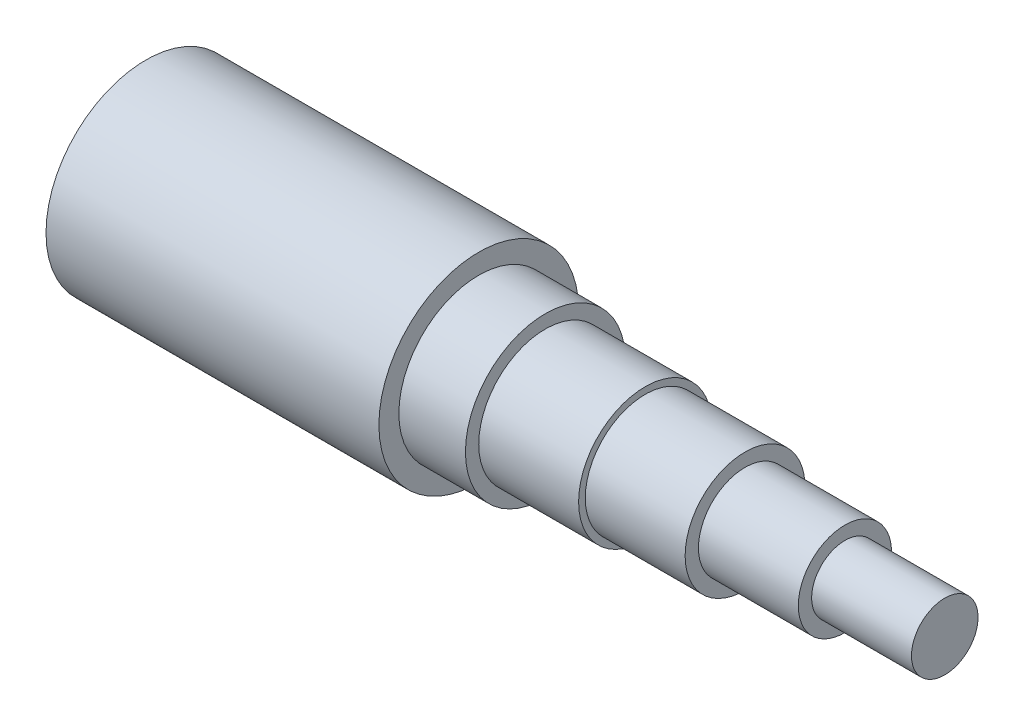
SolidWorks part; units mm, degrees
ref_plane "Front Plane" through (0, 0, 0) normal (0, 0, 1) x (1, 0, 0)
ref_plane "Top Plane" through (0, 0, 0) normal (0, 1, 0) x (1, 0, 0)
ref_plane "Right Plane" through (0, 0, 0) normal (1, 0, 0) x (0, 0, -1)
sketch "Sketch1" plane through (0, 0, 0) normal (0, 0, 1) x (1, 0, 0)
  line L0 (0, 0) -> (130.6843, 0) construction
  line L1 (0, 0) -> (0, 9.525)
  line L2 (0, 9.525) -> (31.75, 9.525)
  line L3 (31.75, 9.525) -> (31.75, 0)
  line L4 (31.75, 7.62) -> (38.1, 7.62)
  line L5 (38.1, 7.62) -> (38.1, 0)
  line L6 (38.1, 6.35) -> (47.625, 6.35)
  line L7 (47.625, 6.35) -> (47.625, 0)
  line L8 (47.625, 5.715) -> (57.15, 5.715)
  line L9 (57.15, 5.715) -> (57.15, 0)
  line L10 (57.15, 4.445) -> (66.675, 4.445)
  line L11 (66.675, 4.445) -> (66.675, 0)
  line L12 (66.675, 3.175) -> (76.2, 3.175)
  line L13 (76.2, 3.175) -> (76.2, 0)
  point P21 (0, -0.5011)
  dimension "D1" = 76.2
  dimension "D2" = 44.45
  dimension "D3" = 9.525
  dimension "D4" = 9.525
  dimension "D5" = 9.525
  dimension "D6" = 9.525
  dimension "D8" = 19.05
  dimension "D9" = 15.24
  dimension "D10" = 12.7
  dimension "D11" = 11.43
  dimension "D12" = 8.89
  dimension "D13" = 6.35
revolve "Revolve2" add sketch "Sketch1" angle 360 about L0
